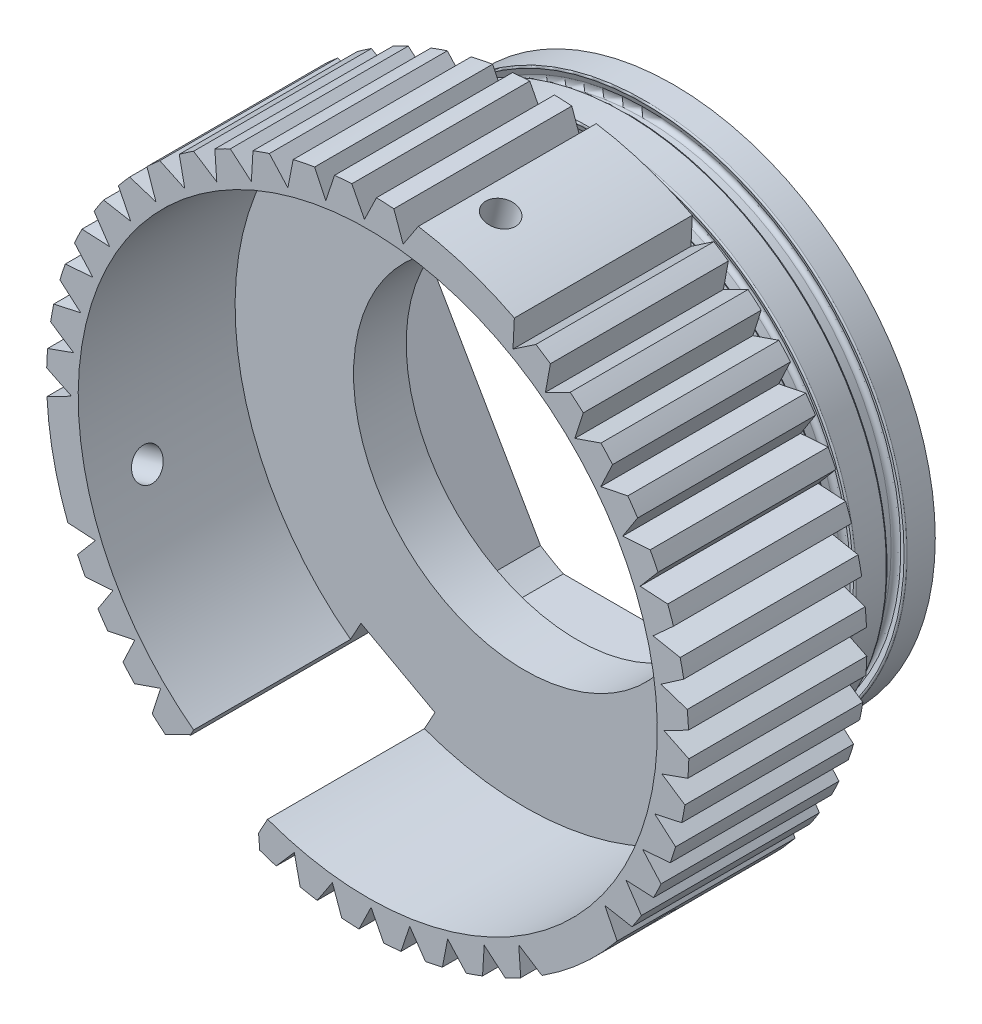
SolidWorks part; units mm, degrees
material "VeroWhite Plus"
ref_plane "Front Plane" through (0, 0, 0) normal (0, 0, 1) x (1, 0, 0)
ref_plane "Top Plane" through (0, 0, 0) normal (0, 1, 0) x (1, 0, 0)
ref_plane "Right Plane" through (0, 0, 0) normal (1, 0, 0) x (0, 0, -1)
sketch "Sketch1" plane through (0, 0, 0) normal (0, 0, 1) x (1, 0, 0)
  circle A0 centre (0, 0) radius 24.875
  dimension "D1" = 49.75
extrude "Boss-Extrude1" add sketch "Sketch1" along normal blind 12.12
sketch "Sketch2" plane through (0, 0, 0) normal (0, 1, 0) x (1, 0, 0)
  line L0 (24.875, -12.12) -> (24.875, 0) construction
  line L1 (24.875, -12.12) -> (24.875, -4.6413) construction
  line L2 (24.6963, -4.5253) -> (24.1354, -4.7751)
  line L3 (23.5771, -4.4125) -> (23.5771, -2.8969)
  line L4 (16.2677, -3.6547) -> (30.8864, -3.6547) construction
  line L5 (24.6963, -2.7841) -> (24.1354, -2.5343)
  line L6 (24.875, -4.6413) -> (24.875, -2.6681)
  line L7 (0, 0) -> (0, -23.2204) construction
  line L8 (23.9739, -2.5) -> (24.1021, -2.5) construction
  line L9 (24.875, 0) -> (-24.875, 0) construction
  line L10 (23.5771, -4.4125) -> (23.5771, -5.8363) construction
  line L11 (23.9739, -4.8094) -> (23.5771, -4.8094) construction
  line L12 (23.5771, -6.0594) -> (25.7057, -6.0594) construction
  line L13 (24.6963, -9.3346) -> (24.1354, -9.5844)
  line L14 (23.5771, -7.7062) -> (23.5771, -9.2218)
  line L15 (24.6963, -7.5934) -> (24.1354, -7.3437)
  line L16 (24.875, -7.4774) -> (24.875, -9.4507)
  line L17 (23.9739, -9.6187) -> (22.6786, -9.6187) construction
  arc A0 (24.1354, -4.7751) -> (23.5771, -4.4125) centre (23.9739, -4.4125) cw
  arc A1 (24.6963, -4.5253) -> (24.875, -4.6413) centre (24.748, -4.6413) cw
  circle A2 centre (24.4661, -3.6547) radius 0.889 construction
  arc A3 (24.1354, -2.5343) -> (23.5771, -2.8969) centre (23.9739, -2.8969) ccw
  arc A4 (24.6963, -2.7841) -> (24.875, -2.6681) centre (24.748, -2.6681) ccw
  arc A5 (24.6963, -9.3346) -> (24.875, -9.4507) centre (24.748, -9.4507) cw
  arc A6 (24.1354, -9.5844) -> (23.5771, -9.2218) centre (23.9739, -9.2218) cw
  arc A7 (24.1354, -7.3437) -> (23.5771, -7.7062) centre (23.9739, -7.7062) ccw
  arc A8 (24.6963, -7.5934) -> (24.875, -7.4774) centre (24.748, -7.4774) ccw
  point P8 (23.5771, -3.6547)
  point P15 (23.5771, -3.6547)
  point P46 (25.3551, -3.6547)
  dimension "D3" = 0.3969
  dimension "D4" = 0.127
  dimension "D5" = 1.778
  dimension "D1" = 1.2979
  dimension "D2" = 66
  dimension "D6" = 2.5
  dimension "D7" = 1.25
revolve "Cut-Revolve1" cut sketch "Sketch2" angle 360 about L7
sketch "Sketch6" plane through (0, 0, 12.12) normal (0, 0, 1) x (1, 0, 0)
  circle A0 centre (0, 0) radius 30.5
  dimension "D1" = 61
extrude "Boss-Extrude2" add sketch "Sketch6" along normal blind 2
sketch "Sketch4" plane through (0, 0, 0) normal (0, 0, 1) x (1, 0, 0)
  circle A0 centre (0, 0) radius 16.25
  dimension "D1" = 32.5
extrude "Cut-Extrude1" cut sketch "Sketch4" along normal through all contours A0
sketch "Sketch5" plane through (0, 0, 0) normal (0, 0, -1) x (-1, 0, 0)
  line L0 (17.7535, 10.25) -> (12.5394, 19.2812) construction
  line L7 (10.4283, 20.5) -> (0, 20.5) construction
  line L8 (22.9677, 1.2188) -> (17.7535, 10.25) construction
  line L9 (17.7535, -10.25) -> (22.9677, -1.2188) construction
  line L10 (12.5394, -19.2812) -> (17.7535, -10.25) construction
  line L11 (0, -20.5) -> (10.4283, -20.5) construction
  line L12 (-10.4283, -20.5) -> (0, -20.5) construction
  line L13 (-17.7535, -10.25) -> (-12.5394, -19.2812) construction
  line L14 (-17.7535, 10.25) -> (-22.9677, 1.2188) construction
  line L15 (-22.9677, -1.2188) -> (-17.7535, -10.25) construction
  line L16 (0, 20.5) -> (-10.4283, 20.5) construction
  line L17 (-12.5394, 19.2812) -> (-17.7535, 10.25) construction
  line L18 (17.8401, 10.3) -> (12.614, 19.3519)
  line L19 (10.4523, 20.6) -> (0, 20.6)
  line L20 (0, 20.6) -> (-10.4523, 20.6)
  line L21 (-12.614, 19.3519) -> (-17.8401, 10.3)
  line L22 (-17.8401, 10.3) -> (-23.0663, 1.2481)
  line L23 (-23.0663, -1.2481) -> (-17.8401, -10.3)
  line L24 (-17.8401, -10.3) -> (-12.614, -19.3519)
  line L25 (-10.4523, -20.6) -> (0, -20.6)
  line L26 (0, -20.6) -> (10.4523, -20.6)
  line L27 (12.614, -19.3519) -> (17.8401, -10.3)
  line L28 (17.8401, -10.3) -> (23.0663, -1.2481)
  line L29 (23.0663, 1.2481) -> (17.8401, 10.3)
  arc A1 (12.5394, 19.2812) -> (10.4283, 20.5) centre (0, 0) ccw construction
  arc A2 (17.7535, 10.25) -> (0, 20.5) centre (0, 0) ccw construction
  arc A3 (22.9677, -1.2188) -> (22.9677, 1.2188) centre (0, 0) ccw construction
  arc A4 (17.7535, -10.25) -> (17.7535, 10.25) centre (0, 0) ccw construction
  arc A5 (0, -20.5) -> (17.7535, -10.25) centre (0, 0) ccw construction
  arc A6 (10.4283, -20.5) -> (12.5394, -19.2812) centre (0, 0) ccw construction
  arc A7 (-17.7535, -10.25) -> (0, -20.5) centre (0, 0) ccw construction
  arc A8 (-12.5394, -19.2812) -> (-10.4283, -20.5) centre (0, 0) ccw construction
  arc A9 (-22.9677, 1.2188) -> (-22.9677, -1.2188) centre (0, 0) ccw construction
  arc A10 (-17.7535, 10.25) -> (-17.7535, -10.25) centre (0, 0) ccw construction
  arc A11 (-10.4283, 20.5) -> (-12.5394, 19.2812) centre (0, 0) ccw construction
  arc A12 (0, 20.5) -> (-17.7535, 10.25) centre (0, 0) ccw construction
  arc A13 (12.614, 19.3519) -> (10.4523, 20.6) centre (0, 0) ccw
  arc A14 (-10.4523, 20.6) -> (-12.614, 19.3519) centre (0, 0) ccw
  arc A15 (-23.0663, 1.2481) -> (-23.0663, -1.2481) centre (0, 0) ccw
  arc A16 (-12.614, -19.3519) -> (-10.4523, -20.6) centre (0, 0) ccw
  arc A17 (10.4523, -20.6) -> (12.614, -19.3519) centre (0, 0) ccw
  arc A18 (23.0663, -1.2481) -> (23.0663, 1.2481) centre (0, 0) ccw
  circle M1 centre (0, 0) radius 16.25
  dimension "D1" = 0.1
extrude "Cut-Extrude2" cut sketch "Sketch5" against normal offset from surface (9.12 mm away) 5 contours L28 A18 L29 L18 A13 L19 L20 A14 L21 L22 A15 L23 L24 A16 L25 L26 A17 L27 M1
sketch "Sketch11" plane through (0, 0, 14.12) normal (0, 0, 1) x (1, 0, 0)
  circle A0 centre (0, 0) radius 27.5
  circle A1 centre (0, 0) radius 30.5
  circle A2 centre (0, 0) radius 30.5
  dimension "D1" = 0
  dimension "D2" = 3
extrude "Boss-Extrude5" add sketch "Sketch11" along normal blind 70
ref_plane "Plane2" through (30.5, 0, 0) normal (1, 0, 0) x (0, 0, -1)
sketch "Sketch14" plane through (0, 0, 84.12) normal (0, 0, 1) x (1, 0, 0)
  line L0 (9.9131, 31.394) -> (7.112, 32.1446) construction
  line L1 (11.113, 31.0725) -> (5.9121, 32.4661) construction
  line L2 (8.5126, 31.7693) -> (0, 0) construction
  line L3 (0, 0) -> (-6.2397, 29.8549) construction
  line L4 (0, 0) -> (-5.194, 30.0545) construction
  line L5 (0, 0) -> (-4.3196, 30.1926) construction
  line L6 (-10.1149, 29.8793) -> (-7.5851, 27.0901) construction
  line L8 (-4.9343, 30.0982) -> (-4.1426, 28.9552) construction
  line L9 (-4.1426, 28.9552) -> (-3.7032, 30.2744) construction
  line L10 (5.9121, 32.4661) -> (4.002, 25.3375) construction
  line L11 (11.113, 31.0725) -> (9.4356, 24.8123) construction
  line L12 (-32.4661, -5.9121) -> (-31.0725, -11.113) construction
  line L13 (-32.1446, -7.112) -> (-31.394, -9.9132) construction
  line L14 (22.2314, -24.282) -> (24.282, -22.2314) construction
  line L15 (-31.7693, -8.5126) -> (0, 0) construction
  line L16 (0, 0) -> (23.2567, -23.2567) construction
  line L17 (25.1604, -21.3531) -> (18.9649, -15.1575) construction
  line L18 (21.3531, -25.1604) -> (14.6891, -18.4965) construction
  line L19 (-32.4661, -5.9121) -> (-24.142, -3.6817) construction
  line L20 (-31.0725, -11.113) -> (-21.737, -8.6116) construction
  line L22 (-0.9635, 30.4848) -> (-0.3278, 29.2482) construction
  line L23 (-0.3278, 29.2482) -> (0.2801, 30.4987) construction
  line L25 (3.0238, 30.3497) -> (3.4927, 29.0407) construction
  line L26 (3.4927, 29.0407) -> (4.2586, 30.2012) construction
  line L28 (14.408, 26.8823) -> (14.3402, 25.4935) construction
  line L29 (14.3402, 25.4935) -> (15.4919, 26.2726) construction
  line L31 (17.7936, 24.7717) -> (17.5451, 23.4037) construction
  line L32 (17.5451, 23.4037) -> (18.7887, 24.0257) construction
  line L34 (20.8747, 22.2373) -> (20.4498, 20.9133) construction
  line L35 (20.4498, 20.9133) -> (21.7639, 21.3678) construction
  line L37 (23.5987, 19.3223) -> (23.0046, 18.0652) construction
  line L38 (23.0046, 18.0652) -> (24.3668, 18.3442) construction
  line L40 (25.9188, 16.0768) -> (25.1658, 14.9079) construction
  line L41 (25.1658, 14.9079) -> (26.5527, 15.0068) construction
  line L43 (27.7956, 12.5562) -> (26.8963, 11.4956) construction
  line L44 (26.8963, 11.4956) -> (28.2843, 11.4126) construction
  line L46 (29.1967, 8.8207) -> (28.1667, 7.8866) construction
  line L47 (28.1667, 7.8866) -> (29.532, 7.6231) construction
  line L49 (30.0982, 4.9343) -> (28.9552, 4.1426) construction
  line L50 (28.9552, 4.1426) -> (30.2744, 3.7032) construction
  line L52 (30.4848, 0.9635) -> (29.2482, 0.3278) construction
  line L53 (29.2482, 0.3278) -> (30.4987, -0.2801) construction
  line L55 (30.3497, -3.0238) -> (29.0407, -3.4927) construction
  line L56 (29.0407, -3.4927) -> (30.2012, -4.2586) construction
  line L58 (29.6954, -6.9594) -> (28.3364, -7.2534) construction
  line L59 (28.3364, -7.2534) -> (29.387, -8.1642) construction
  line L61 (28.533, -10.7759) -> (27.1472, -10.89) construction
  line L62 (27.1472, -10.89) -> (28.0699, -11.9301) construction
  line L64 (26.8823, -14.408) -> (25.4935, -14.3402) construction
  line L65 (25.4935, -14.3402) -> (26.2726, -15.4919) construction
  line L67 (24.7717, -17.7936) -> (23.4037, -17.5451) construction
  line L68 (23.4037, -17.5451) -> (24.0257, -18.7887) construction
  line L70 (16.0768, -25.9189) -> (14.9079, -25.1658) construction
  line L71 (14.9079, -25.1658) -> (15.0068, -26.5527) construction
  line L73 (12.5562, -27.7956) -> (11.4956, -26.8964) construction
  line L74 (11.4956, -26.8964) -> (11.4126, -28.2843) construction
  line L76 (8.8207, -29.1967) -> (7.8866, -28.1667) construction
  line L77 (7.8866, -28.1667) -> (7.6231, -29.532) construction
  line L79 (4.9343, -30.0982) -> (4.1426, -28.9552) construction
  line L80 (4.1426, -28.9552) -> (3.7032, -30.2744) construction
  line L82 (0.9635, -30.4848) -> (0.3278, -29.2482) construction
  line L83 (0.3278, -29.2482) -> (-0.2801, -30.4987) construction
  line L85 (-3.0238, -30.3497) -> (-3.4927, -29.0407) construction
  line L86 (-3.4927, -29.0407) -> (-4.2586, -30.2012) construction
  line L88 (-6.9594, -29.6954) -> (-7.2534, -28.3364) construction
  line L89 (-7.2534, -28.3364) -> (-8.1642, -29.387) construction
  line L91 (-10.7759, -28.533) -> (-10.89, -27.1472) construction
  line L92 (-10.89, -27.1472) -> (-11.9301, -28.0699) construction
  line L94 (-14.408, -26.8823) -> (-14.3402, -25.4935) construction
  line L95 (-14.3402, -25.4935) -> (-15.4919, -26.2726) construction
  line L97 (-17.7936, -24.7717) -> (-17.5451, -23.4037) construction
  line L98 (-17.5451, -23.4037) -> (-18.7887, -24.0257) construction
  line L100 (-20.8747, -22.2373) -> (-20.4498, -20.9133) construction
  line L101 (-20.4498, -20.9133) -> (-21.7639, -21.3678) construction
  line L103 (-23.5987, -19.3223) -> (-23.0046, -18.0652) construction
  line L104 (-23.0046, -18.0652) -> (-24.3668, -18.3442) construction
  line L106 (-25.9188, -16.0768) -> (-25.1658, -14.9079) construction
  line L107 (-25.1658, -14.9079) -> (-26.5527, -15.0068) construction
  line L109 (-27.7956, -12.5562) -> (-26.8964, -11.4956) construction
  line L110 (-26.8964, -11.4956) -> (-28.2843, -11.4126) construction
  line L112 (-30.4848, -0.9635) -> (-29.2482, -0.3278) construction
  line L113 (-29.2482, -0.3278) -> (-30.4987, 0.2801) construction
  line L115 (-30.3497, 3.0238) -> (-29.0407, 3.4927) construction
  line L116 (-29.0407, 3.4927) -> (-30.2012, 4.2586) construction
  line L118 (-29.6954, 6.9594) -> (-28.3364, 7.2534) construction
  line L119 (-28.3364, 7.2534) -> (-29.387, 8.1642) construction
  line L121 (-28.533, 10.7759) -> (-27.1472, 10.89) construction
  line L122 (-27.1472, 10.89) -> (-28.07, 11.9301) construction
  line L124 (-26.8823, 14.408) -> (-25.4935, 14.3402) construction
  line L125 (-25.4935, 14.3402) -> (-26.2726, 15.4919) construction
  line L127 (-24.7717, 17.7936) -> (-23.4037, 17.5451) construction
  line L128 (-23.4037, 17.5451) -> (-24.0257, 18.7887) construction
  line L130 (-22.2373, 20.8747) -> (-20.9133, 20.4498) construction
  line L131 (-20.9133, 20.4498) -> (-21.3678, 21.7639) construction
  line L133 (-19.3223, 23.5987) -> (-18.0652, 23.0046) construction
  line L134 (-18.0652, 23.0046) -> (-18.3442, 24.3668) construction
  line L136 (-16.0768, 25.9188) -> (-14.9079, 25.1658) construction
  line L137 (-14.9079, 25.1658) -> (-15.0068, 26.5527) construction
  line L139 (-12.5562, 27.7955) -> (-11.4956, 26.8963) construction
  line L140 (-11.4956, 26.8963) -> (-11.4126, 28.2843) construction
  line L142 (-8.8207, 29.1967) -> (-7.8866, 28.1667) construction
  line L143 (-7.8866, 28.1667) -> (-7.6231, 29.532) construction
  line L146 (-3.9843, 27.8484) -> (-3.1555, 30.3363)
  line L148 (-1.5142, 30.4624) -> (-0.3152, 28.1302)
  line L149 (-0.3152, 28.1302) -> (0.8311, 30.4887)
  line L151 (2.4749, 30.3994) -> (3.3592, 27.9307)
  line L152 (3.3592, 27.9307) -> (4.8036, 30.1194)
  line L154 (13.9199, 27.1383) -> (13.7921, 24.5191)
  line L155 (13.7921, 24.5191) -> (15.9641, 25.9884)
  line L157 (17.343, 25.0892) -> (16.8745, 22.5091)
  line L158 (16.8745, 22.5091) -> (19.2197, 23.6823)
  line L160 (20.4695, 22.6109) -> (19.6681, 20.114)
  line L161 (19.6681, 20.114) -> (22.1465, 20.971)
  line L163 (23.2457, 19.7456) -> (22.1253, 17.3747)
  line L164 (22.1253, 17.3747) -> (24.6943, 17.9009)
  line L166 (25.6241, 16.5425) -> (24.2038, 14.3381)
  line L167 (24.2038, 14.3381) -> (26.8195, 14.5245)
  line L169 (27.5641, 13.0564) -> (25.8683, 11.0562)
  line L170 (25.8683, 11.0562) -> (28.4859, 10.8996)
  line L172 (29.0325, 9.3468) -> (27.0901, 7.5851)
  line L173 (27.0901, 7.5851) -> (29.6649, 7.0882)
  line L175 (30.0041, 5.4774) -> (27.8484, 3.9843)
  line L176 (27.8484, 3.9843) -> (30.3363, 3.1555)
  line L178 (30.4624, 1.5142) -> (28.1302, 0.3152)
  line L179 (28.1302, 0.3152) -> (30.4887, -0.8312)
  line L181 (30.3994, -2.4749) -> (27.9307, -3.3592)
  line L182 (27.9307, -3.3592) -> (30.1194, -4.8036)
  line L184 (29.8163, -6.4217) -> (27.2533, -6.9761)
  line L185 (27.2533, -6.9761) -> (29.2347, -8.6939)
  line L187 (28.723, -10.2585) -> (26.1095, -10.4737)
  line L188 (26.1095, -10.4737) -> (27.8498, -12.4354)
  line L190 (27.1383, -13.9199) -> (24.5191, -13.7921)
  line L191 (24.5191, -13.7921) -> (25.9884, -15.9641)
  line L193 (25.0892, -17.3431) -> (22.5091, -16.8745)
  line L194 (22.5091, -16.8745) -> (23.6823, -19.2197)
  line L196 (16.5425, -25.6241) -> (14.3381, -24.2039)
  line L197 (14.3381, -24.2039) -> (14.5245, -26.8195)
  line L199 (13.0564, -27.5641) -> (11.0562, -25.8683)
  line L200 (11.0562, -25.8683) -> (10.8996, -28.4859)
  line L202 (9.3468, -29.0325) -> (7.5851, -27.0901)
  line L203 (7.5851, -27.0901) -> (7.0882, -29.6649)
  line L205 (5.4774, -30.0041) -> (3.9843, -27.8484)
  line L206 (3.9843, -27.8484) -> (3.1555, -30.3363)
  line L208 (1.5142, -30.4624) -> (0.3152, -28.1302)
  line L209 (0.3152, -28.1302) -> (-0.8312, -30.4887)
  line L211 (-2.4749, -30.3994) -> (-3.3592, -27.9307)
  line L212 (-3.3592, -27.9307) -> (-4.8036, -30.1194)
  line L214 (-6.4217, -29.8163) -> (-6.9761, -27.2533)
  line L215 (-6.9761, -27.2533) -> (-8.6939, -29.2347)
  line L217 (-10.2585, -28.723) -> (-10.4737, -26.1096)
  line L218 (-10.4737, -26.1096) -> (-12.4354, -27.8498)
  line L220 (-13.9199, -27.1383) -> (-13.7921, -24.5191)
  line L221 (-13.7921, -24.5191) -> (-15.9641, -25.9884)
  line L223 (-17.3431, -25.0892) -> (-16.8745, -22.5091)
  line L224 (-16.8745, -22.5091) -> (-19.2197, -23.6823)
  line L226 (-20.4695, -22.6108) -> (-19.6682, -20.114)
  line L227 (-19.6682, -20.114) -> (-22.1465, -20.971)
  line L229 (-23.2457, -19.7456) -> (-22.1253, -17.3747)
  line L230 (-22.1253, -17.3747) -> (-24.6943, -17.9009)
  line L232 (-25.6241, -16.5425) -> (-24.2039, -14.3381)
  line L233 (-24.2039, -14.3381) -> (-26.8195, -14.5245)
  line L235 (-27.5641, -13.0564) -> (-25.8683, -11.0562)
  line L236 (-25.8683, -11.0562) -> (-28.4859, -10.8996)
  line L238 (-30.4624, -1.5142) -> (-28.1302, -0.3152)
  line L239 (-28.1302, -0.3152) -> (-30.4887, 0.8311)
  line L241 (-30.3994, 2.4749) -> (-27.9307, 3.3592)
  line L242 (-27.9307, 3.3592) -> (-30.1194, 4.8036)
  line L244 (-29.8163, 6.4217) -> (-27.2533, 6.9761)
  line L245 (-27.2533, 6.9761) -> (-29.2347, 8.6939)
  line L247 (-28.723, 10.2585) -> (-26.1096, 10.4737)
  line L248 (-26.1096, 10.4737) -> (-27.8498, 12.4354)
  line L250 (-27.1383, 13.9199) -> (-24.5191, 13.7921)
  line L251 (-24.5191, 13.7921) -> (-25.9884, 15.9641)
  line L253 (-25.0892, 17.343) -> (-22.5091, 16.8745)
  line L254 (-22.5091, 16.8745) -> (-23.6823, 19.2197)
  line L256 (-22.6109, 20.4695) -> (-20.114, 19.6682)
  line L257 (-20.114, 19.6682) -> (-20.971, 22.1465)
  line L259 (-19.7456, 23.2457) -> (-17.3747, 22.1253)
  line L260 (-17.3747, 22.1253) -> (-17.9009, 24.6943)
  line L262 (-16.5425, 25.6241) -> (-14.3381, 24.2038)
  line L263 (-14.3381, 24.2038) -> (-14.5245, 26.8195)
  line L265 (-13.0564, 27.5641) -> (-11.0562, 25.8683)
  line L266 (-11.0562, 25.8683) -> (-10.8996, 28.4859)
  line L268 (-9.3468, 29.0325) -> (-7.5851, 27.0901)
  line L269 (-7.5851, 27.0901) -> (-7.0882, 29.6649)
  line L270 (-25.8683, -11.0562) -> (-29.6271, -10.8314) construction
  line L271 (-26.8964, -11.4956) -> (-28.8494, -11.3788) construction
  line L272 (-28.3035, -13.9284) -> (-25.8683, -11.0562) construction
  line L273 (-28.1617, -12.988) -> (-26.8964, -11.4956) construction
  line L274 (-24.2039, -14.3381) -> (-27.9599, -14.6058) construction
  line L275 (-25.1658, -14.9079) -> (-27.1174, -15.047) construction
  line L276 (-26.2433, -17.5036) -> (-24.2039, -14.3381) construction
  line L277 (-26.2255, -16.5527) -> (-25.1658, -14.9079) construction
  line L278 (-3.5243, 30.8114) -> (-5.2566, 30.5636) construction
  line L279 (-22.1253, -17.3747) -> (-25.8143, -18.1304) construction
  line L280 (-23.0046, -18.0652) -> (-24.9214, -18.4578) construction
  line L281 (-23.8405, -19.8342) -> (-23.0046, -18.0652) construction
  line L282 (-23.7341, -20.7793) -> (-22.1253, -17.3747) construction
  line L283 (-19.6682, -20.114) -> (-23.2269, -21.3447) construction
  line L284 (-20.4498, -20.9133) -> (-22.2989, -21.5528) construction
  line L285 (-21.0477, -22.7763) -> (-20.4498, -20.9133) construction
  line L286 (-20.8188, -23.6994) -> (-19.6682, -20.114) construction
  line L287 (-16.8745, -22.5091) -> (-20.2422, -24.1938) construction
  line L288 (-17.5451, -23.4037) -> (-19.2949, -24.279) construction
  line L289 (-17.8947, -25.3287) -> (-17.5451, -23.4037) construction
  line L290 (-17.5473, -26.2141) -> (-16.8745, -22.5091) construction
  line L291 (-13.7921, -24.5191) -> (-16.9111, -26.629) construction
  line L292 (-14.3402, -25.4935) -> (-15.9608, -26.5898) construction
  line L293 (-13.9756, -28.2802) -> (-13.7921, -24.5191) construction
  line L294 (-14.4356, -27.4478) -> (-14.3402, -25.4935) construction
  line L295 (-11.0562, 25.8683) -> (-10.8314, 29.6271) construction
  line L296 (-10.4737, -26.1096) -> (-13.2906, -28.6085) construction
  line L297 (-10.89, -27.1472) -> (-12.3536, -28.4456) construction
  line L298 (-10.7294, -29.0972) -> (-10.89, -27.1472) construction
  line L299 (-10.1647, -29.8624) -> (-10.4737, -26.1096) construction
  line L300 (-6.9761, -27.2533) -> (-9.4428, -30.0985) construction
  line L301 (-7.2534, -28.3364) -> (-8.535, -29.8147) construction
  line L302 (-6.8397, -30.2487) -> (-7.2534, -28.3364) construction
  line L303 (-6.1799, -30.9337) -> (-6.9761, -27.2533) construction
  line L304 (-3.3592, -27.9307) -> (-5.4333, -31.0735) construction
  line L305 (-28.8494, -11.3788) -> (-28.1617, -12.988) construction
  line L306 (-29.6271, -10.8314) -> (-28.3035, -13.9284) construction
  line L307 (-27.1174, -15.047) -> (-26.2255, -16.5527) construction
  line L308 (-27.9599, -14.6058) -> (-26.2433, -17.5036) construction
  line L309 (-23.2269, -21.3447) -> (-20.8188, -23.6994) construction
  line L310 (-22.2989, -21.5528) -> (-21.0477, -22.7763) construction
  line L311 (-25.8143, -18.1304) -> (-23.7341, -20.7793) construction
  line L312 (-24.9214, -18.4578) -> (-23.8405, -19.8342) construction
  line L313 (-19.2949, -24.279) -> (-17.8947, -25.3287) construction
  line L314 (-20.2422, -24.1938) -> (-17.5473, -26.2141) construction
  line L315 (-15.9608, -26.5898) -> (-14.4356, -27.4478) construction
  line L316 (-16.9111, -26.629) -> (-13.9756, -28.2802) construction
  line L317 (-12.3536, -28.4456) -> (-10.7294, -29.0972) construction
  line L318 (-13.2906, -28.6085) -> (-10.1647, -29.8624) construction
  line L319 (-9.4428, -30.0985) -> (-6.1799, -30.9337) construction
  line L320 (-8.535, -29.8147) -> (-6.8397, -30.2487) construction
  line L321 (-3.4927, -29.0407) -> (-4.5704, -30.6737) construction
  line L322 (-2.8329, -30.8827) -> (-3.4927, -29.0407) construction
  line L323 (-2.0894, -31.4757) -> (-3.3592, -27.9307) construction
  line L324 (-4.5704, -30.6737) -> (-2.8329, -30.8827) construction
  line L325 (-5.4333, -31.0735) -> (-2.0894, -31.4757) construction
  line L326 (0.3152, -28.1302) -> (-1.3309, -31.5169) construction
  line L327 (0.3278, -29.2482) -> (-0.5276, -31.0079) construction
  line L328 (1.2223, -30.9883) -> (0.3278, -29.2482) construction
  line L329 (2.0369, -31.4792) -> (0.3152, -28.1302) construction
  line L330 (-0.5276, -31.0079) -> (1.2223, -30.9883) construction
  line L331 (-1.3309, -31.5169) -> (2.0369, -31.4792) construction
  line L332 (3.9843, -27.8484) -> (2.7942, -31.421) construction
  line L333 (4.1426, -28.9552) -> (3.5243, -30.8114) construction
  line L334 (5.2566, -30.5636) -> (4.1426, -28.9552) construction
  line L335 (6.1283, -30.944) -> (3.9843, -27.8484) construction
  line L336 (3.5243, -30.8114) -> (5.2566, -30.5636) construction
  line L337 (2.7942, -31.421) -> (6.1283, -30.944) construction
  line L338 (7.5851, -27.0901) -> (6.8716, -30.7875) construction
  line L339 (7.8866, -28.1667) -> (7.5158, -30.0878) construction
  line L340 (9.201, -29.616) -> (7.8866, -28.1667) construction
  line L341 (10.1149, -29.8793) -> (7.5851, -27.0901) construction
  line L342 (6.8716, -30.7875) -> (10.1149, -29.8793) construction
  line L343 (7.5158, -30.0878) -> (9.201, -29.616) construction
  line L344 (11.0562, -25.8683) -> (10.8314, -29.6271) construction
  line L345 (11.4956, -26.8964) -> (11.3788, -28.8494) construction
  line L346 (12.988, -28.1617) -> (11.4956, -26.8964) construction
  line L347 (13.9284, -28.3035) -> (11.0562, -25.8683) construction
  line L348 (10.8314, -29.6271) -> (13.9284, -28.3035) construction
  line L349 (11.3788, -28.8494) -> (12.988, -28.1617) construction
  line L350 (14.3381, -24.2039) -> (14.6058, -27.9599) construction
  line L351 (14.9079, -25.1658) -> (15.047, -27.1174) construction
  line L352 (16.5527, -26.2255) -> (14.9079, -25.1658) construction
  line L353 (17.5036, -26.2433) -> (14.3381, -24.2039) construction
  line L354 (15.047, -27.1174) -> (16.5527, -26.2255) construction
  line L355 (14.6058, -27.9599) -> (17.5036, -26.2433) construction
  line L356 (22.5091, -16.8745) -> (24.1938, -20.2422) construction
  line L357 (23.4037, -17.5451) -> (24.279, -19.2949) construction
  line L358 (25.3287, -17.8947) -> (23.4037, -17.5451) construction
  line L359 (26.2141, -17.5473) -> (22.5091, -16.8745) construction
  line L360 (24.5191, -13.7921) -> (26.629, -16.9111) construction
  line L361 (25.4935, -14.3402) -> (26.5898, -15.9608) construction
  line L362 (27.4478, -14.4356) -> (25.4935, -14.3402) construction
  line L363 (28.2802, -13.9756) -> (24.5191, -13.7921) construction
  line L364 (26.5898, -15.9608) -> (27.4478, -14.4356) construction
  line L365 (26.629, -16.9111) -> (28.2802, -13.9756) construction
  line L366 (24.279, -19.2949) -> (25.3287, -17.8947) construction
  line L367 (24.1938, -20.2422) -> (26.2141, -17.5473) construction
  line L368 (26.1095, -10.4737) -> (28.6085, -13.2906) construction
  line L369 (27.1472, -10.89) -> (28.4456, -12.3536) construction
  line L370 (28.4456, -12.3536) -> (29.0972, -10.7294) construction
  line L371 (29.0972, -10.7294) -> (27.1472, -10.89) construction
  line L372 (29.8624, -10.1647) -> (26.1095, -10.4737) construction
  line L373 (28.6085, -13.2906) -> (29.8624, -10.1647) construction
  line L374 (27.2533, -6.9761) -> (30.0985, -9.4428) construction
  line L375 (28.3364, -7.2534) -> (29.8147, -8.535) construction
  line L376 (30.2487, -6.8397) -> (28.3364, -7.2534) construction
  line L377 (30.9337, -6.1799) -> (27.2533, -6.9761) construction
  line L378 (29.8147, -8.535) -> (30.2487, -6.8397) construction
  line L379 (30.0985, -9.4428) -> (30.9337, -6.1799) construction
  line L380 (27.9307, -3.3592) -> (31.0735, -5.4333) construction
  line L381 (29.0407, -3.4927) -> (30.6737, -4.5704) construction
  line L382 (30.6737, -4.5704) -> (30.8827, -2.8329) construction
  line L383 (31.0735, -5.4333) -> (31.4757, -2.0894) construction
  line L384 (30.8827, -2.8329) -> (29.0407, -3.4927) construction
  line L385 (31.4757, -2.0894) -> (27.9307, -3.3592) construction
  line L386 (28.1302, 0.3152) -> (31.5169, -1.3309) construction
  line L387 (29.2482, 0.3278) -> (31.0079, -0.5276) construction
  line L388 (30.9882, 1.2223) -> (29.2482, 0.3278) construction
  line L389 (31.4791, 2.0369) -> (28.1302, 0.3152) construction
  line L390 (27.8484, 3.9843) -> (31.421, 2.7942) construction
  line L391 (28.9552, 4.1426) -> (30.8114, 3.5243) construction
  line L392 (30.5636, 5.2566) -> (28.9552, 4.1426) construction
  line L393 (30.944, 6.1283) -> (27.8484, 3.9843) construction
  line L394 (27.0901, 7.5851) -> (30.7874, 6.8716) construction
  line L395 (28.1667, 7.8866) -> (30.0878, 7.5158) construction
  line L396 (30.0878, 7.5158) -> (29.616, 9.201) construction
  line L397 (30.7874, 6.8716) -> (29.8793, 10.1149) construction
  line L398 (31.421, 2.7942) -> (30.944, 6.1283) construction
  line L399 (30.8114, 3.5243) -> (30.5636, 5.2566) construction
  line L400 (31.0079, -0.5276) -> (30.9882, 1.2223) construction
  line L401 (31.5169, -1.3309) -> (31.4791, 2.0369) construction
  line L402 (29.8793, 10.1149) -> (27.0901, 7.5851) construction
  line L403 (29.616, 9.201) -> (28.1667, 7.8866) construction
  line L404 (25.8683, 11.0562) -> (29.6271, 10.8314) construction
  line L405 (26.8963, 11.4956) -> (28.8494, 11.3788) construction
  line L406 (28.1616, 12.988) -> (26.8963, 11.4956) construction
  line L407 (28.3035, 13.9284) -> (25.8683, 11.0562) construction
  line L408 (24.2038, 14.3381) -> (27.9599, 14.6058) construction
  line L409 (25.1658, 14.9079) -> (27.1174, 15.047) construction
  line L410 (27.1174, 15.047) -> (26.2254, 16.5527) construction
  line L411 (26.2254, 16.5527) -> (25.1658, 14.9079) construction
  line L412 (26.2433, 17.5036) -> (24.2038, 14.3381) construction
  line L413 (27.9599, 14.6058) -> (26.2433, 17.5036) construction
  line L414 (28.8494, 11.3788) -> (28.1616, 12.988) construction
  line L415 (29.6271, 10.8314) -> (28.3035, 13.9284) construction
  line L416 (20.8188, 23.6994) -> (19.6681, 20.114) construction
  line L417 (21.0477, 22.7763) -> (20.4498, 20.9133) construction
  line L418 (20.4498, 20.9133) -> (22.2989, 21.5528) construction
  line L419 (19.6681, 20.114) -> (23.2269, 21.3447) construction
  line L420 (23.7341, 20.7793) -> (22.1253, 17.3747) construction
  line L421 (23.8405, 19.8342) -> (23.0046, 18.0652) construction
  line L422 (23.0046, 18.0652) -> (24.9214, 18.4578) construction
  line L423 (22.1253, 17.3747) -> (25.8143, 18.1304) construction
  line L424 (24.9214, 18.4578) -> (23.8405, 19.8342) construction
  line L425 (25.8143, 18.1304) -> (23.7341, 20.7793) construction
  line L426 (23.2269, 21.3447) -> (20.8188, 23.6994) construction
  line L427 (22.2989, 21.5528) -> (21.0477, 22.7763) construction
  line L428 (13.9756, 28.2802) -> (13.7921, 24.5191) construction
  line L429 (14.4356, 27.4478) -> (14.3402, 25.4935) construction
  line L430 (14.3402, 25.4935) -> (15.9608, 26.5898) construction
  line L431 (13.7921, 24.5191) -> (16.9111, 26.629) construction
  line L432 (17.5473, 26.2141) -> (16.8745, 22.5091) construction
  line L433 (17.8947, 25.3287) -> (17.5451, 23.4037) construction
  line L434 (17.5451, 23.4037) -> (19.2949, 24.279) construction
  line L435 (16.8745, 22.5091) -> (20.2422, 24.1938) construction
  line L436 (20.2422, 24.1938) -> (17.5473, 26.2141) construction
  line L437 (19.2949, 24.279) -> (17.8947, 25.3287) construction
  line L438 (16.9111, 26.629) -> (13.9756, 28.2802) construction
  line L439 (15.9608, 26.5898) -> (14.4356, 27.4478) construction
  line L440 (3.3592, 27.9307) -> (5.4333, 31.0735) construction
  line L441 (3.4927, 29.0407) -> (4.5704, 30.6737) construction
  line L442 (2.8329, 30.8827) -> (3.4927, 29.0407) construction
  line L443 (2.0894, 31.4757) -> (3.3592, 27.9307) construction
  line L444 (-0.3152, 28.1302) -> (1.3309, 31.5169) construction
  line L445 (-0.3278, 29.2482) -> (0.5276, 31.0079) construction
  line L446 (-1.2223, 30.9882) -> (-0.3278, 29.2482) construction
  line L447 (-2.0369, 31.4792) -> (-0.3152, 28.1302) construction
  line L448 (1.3309, 31.5169) -> (-2.0369, 31.4792) construction
  line L449 (0.5276, 31.0079) -> (-1.2223, 30.9882) construction
  line L450 (4.5704, 30.6737) -> (2.8329, 30.8827) construction
  line L451 (5.4333, 31.0735) -> (2.0894, 31.4757) construction
  line L452 (-3.9843, 27.8484) -> (-2.7942, 31.421) construction
  line L453 (-4.1426, 28.9552) -> (-3.5243, 30.8114) construction
  line L454 (-11.4956, 26.8963) -> (-11.3788, 28.8494) construction
  line L455 (-5.2566, 30.5636) -> (-4.1426, 28.9552) construction
  line L456 (-5.0434, 30.0801) -> (-3.9843, 27.8484)
  line L457 (-6.1283, 30.944) -> (-3.9843, 27.8484) construction
  line L458 (-12.988, 28.1616) -> (-11.4956, 26.8963) construction
  line L459 (-7.5851, 27.0901) -> (-6.8716, 30.7875) construction
  line L460 (-7.8866, 28.1667) -> (-7.5158, 30.0878) construction
  line L461 (-7.5158, 30.0878) -> (-9.201, 29.616) construction
  line L462 (-6.8716, 30.7875) -> (-10.1149, 29.8793) construction
  line L463 (-9.201, 29.616) -> (-7.8866, 28.1667) construction
  line L464 (-13.9284, 28.3035) -> (-11.0562, 25.8683) construction
  line L465 (-14.3381, 24.2038) -> (-14.6058, 27.9599) construction
  line L466 (-2.7942, 31.421) -> (-6.1283, 30.944) construction
  line L467 (-14.9079, 25.1658) -> (-15.047, 27.1174) construction
  line L468 (-16.5527, 26.2255) -> (-14.9079, 25.1658) construction
  line L469 (-17.5036, 26.2433) -> (-14.3381, 24.2038) construction
  line L470 (-14.6058, 27.9599) -> (-17.5036, 26.2433) construction
  line L471 (-15.047, 27.1174) -> (-16.5527, 26.2255) construction
  line L472 (-11.3788, 28.8494) -> (-12.988, 28.1616) construction
  line L473 (-10.8314, 29.6271) -> (-13.9284, 28.3035) construction
  line L474 (-17.3747, 22.1253) -> (-18.1304, 25.8143) construction
  line L475 (-18.0652, 23.0046) -> (-18.4578, 24.9214) construction
  line L476 (-19.8342, 23.8405) -> (-18.0652, 23.0046) construction
  line L477 (-20.7793, 23.7341) -> (-17.3747, 22.1253) construction
  line L478 (-18.4578, 24.9214) -> (-19.8342, 23.8405) construction
  line L479 (-18.1304, 25.8143) -> (-20.7793, 23.7341) construction
  line L480 (-21.5528, 22.2989) -> (-22.7763, 21.0477) construction
  line L481 (-21.3447, 23.2269) -> (-23.6994, 20.8188) construction
  line L482 (-20.9133, 20.4498) -> (-21.5528, 22.2989) construction
  line L483 (-22.7763, 21.0477) -> (-20.9133, 20.4498) construction
  line L484 (-20.114, 19.6682) -> (-21.3447, 23.2269) construction
  line L485 (-23.6994, 20.8188) -> (-20.114, 19.6682) construction
  line L486 (-22.5091, 16.8745) -> (-24.1938, 20.2422) construction
  line L487 (-23.4037, 17.5451) -> (-24.279, 19.2949) construction
  line L488 (-25.3287, 17.8947) -> (-23.4037, 17.5451) construction
  line L489 (-26.2141, 17.5473) -> (-22.5091, 16.8745) construction
  line L490 (-24.5191, 13.7921) -> (-26.629, 16.9111) construction
  line L491 (-25.4935, 14.3402) -> (-26.5898, 15.9608) construction
  line L492 (-27.4478, 14.4356) -> (-25.4935, 14.3402) construction
  line L493 (-28.2802, 13.9756) -> (-24.5191, 13.7921) construction
  line L494 (-26.629, 16.9111) -> (-28.2802, 13.9756) construction
  line L495 (-26.5898, 15.9608) -> (-27.4478, 14.4356) construction
  line L496 (-24.1938, 20.2422) -> (-26.2141, 17.5473) construction
  line L497 (-24.279, 19.2949) -> (-25.3287, 17.8947) construction
  line L498 (-26.1096, 10.4737) -> (-28.6085, 13.2906) construction
  line L499 (-27.1472, 10.89) -> (-28.4456, 12.3536) construction
  line L500 (-29.0972, 10.7294) -> (-27.1472, 10.89) construction
  line L501 (-29.8624, 10.1647) -> (-26.1096, 10.4737) construction
  line L502 (-27.2533, 6.9761) -> (-30.0985, 9.4428) construction
  line L503 (-28.3364, 7.2534) -> (-29.8147, 8.535) construction
  line L504 (-30.2487, 6.8397) -> (-28.3364, 7.2534) construction
  line L505 (-30.9337, 6.1799) -> (-27.2533, 6.9761) construction
  line L506 (-30.0985, 9.4428) -> (-30.9337, 6.1799) construction
  line L507 (-29.8147, 8.535) -> (-30.2487, 6.8397) construction
  line L508 (-28.6085, 13.2906) -> (-29.8624, 10.1647) construction
  line L509 (-28.4456, 12.3536) -> (-29.0972, 10.7294) construction
  line L510 (-27.9307, 3.3592) -> (-31.0735, 5.4333) construction
  line L511 (-29.0407, 3.4927) -> (-30.6737, 4.5704) construction
  line L512 (-30.8827, 2.8329) -> (-29.0407, 3.4927) construction
  line L513 (-31.4757, 2.0894) -> (-27.9307, 3.3592) construction
  line L514 (-28.1302, -0.3152) -> (-31.5169, 1.3309) construction
  line L515 (-29.2482, -0.3278) -> (-31.0079, 0.5276) construction
  line L516 (-30.9883, -1.2223) -> (-29.2482, -0.3278) construction
  line L517 (-31.4792, -2.0369) -> (-28.1302, -0.3152) construction
  line L518 (-31.5169, 1.3309) -> (-31.4792, -2.0369) construction
  line L519 (-31.0079, 0.5276) -> (-30.9883, -1.2223) construction
  line L520 (-31.0735, 5.4333) -> (-31.4757, 2.0894) construction
  line L521 (-30.6737, 4.5704) -> (-30.8827, 2.8329) construction
  arc A0 (21.3531, -25.1604) -> (25.1604, -21.3531) centre (0, 0) ccw construction
  arc A1 (-10.2585, -28.723) -> (-8.6939, -29.2347) centre (0, 0) ccw
  circle A2 centre (0, 0) radius 30.5 construction
  arc A3 (-6.4217, -29.8163) -> (-4.8036, -30.1194) centre (0, 0) ccw
  arc A4 (-13.9199, -27.1383) -> (-12.4354, -27.8498) centre (0, 0) ccw
  arc A5 (-17.3431, -25.0892) -> (-15.9641, -25.9884) centre (0, 0) ccw
  arc A6 (-20.4695, -22.6108) -> (-19.2197, -23.6823) centre (0, 0) ccw
  arc A7 (-23.2457, -19.7456) -> (-22.1465, -20.971) centre (0, 0) ccw
  arc A8 (-25.6241, -16.5425) -> (-24.6943, -17.9009) centre (0, 0) ccw
  arc A9 (-27.5641, -13.0564) -> (-26.8195, -14.5245) centre (0, 0) ccw
  arc A10 (-2.4749, -30.3994) -> (-0.8312, -30.4887) centre (0, 0) ccw
  arc A11 (1.5142, -30.4624) -> (3.1555, -30.3363) centre (0, 0) ccw
  arc A12 (5.4774, -30.0041) -> (7.0882, -29.6649) centre (0, 0) ccw
  arc A13 (9.3468, -29.0325) -> (10.8996, -28.4859) centre (0, 0) ccw
  arc A14 (13.0564, -27.5641) -> (14.5245, -26.8195) centre (0, 0) ccw
  arc A15 (16.5425, -25.6241) -> (23.6823, -19.2197) centre (0, 0) ccw
  arc A16 (25.0892, -17.3431) -> (25.9884, -15.9641) centre (0, 0) ccw
  arc A17 (28.723, -10.2585) -> (29.2347, -8.6939) centre (0, 0) ccw
  arc A18 (27.1383, -13.9199) -> (27.8498, -12.4354) centre (0, 0) ccw
  arc A19 (29.8163, -6.4217) -> (30.1194, -4.8036) centre (0, 0) ccw
  arc A20 (30.3994, -2.4749) -> (30.4887, -0.8312) centre (0, 0) ccw
  arc A21 (30.4624, 1.5142) -> (30.3363, 3.1555) centre (0, 0) ccw
  arc A22 (30.0041, 5.4774) -> (29.6649, 7.0882) centre (0, 0) ccw
  arc A23 (29.0325, 9.3468) -> (28.4859, 10.8996) centre (0, 0) ccw
  arc A24 (27.5641, 13.0564) -> (26.8195, 14.5245) centre (0, 0) ccw
  arc A25 (25.6241, 16.5425) -> (24.6943, 17.9009) centre (0, 0) ccw
  arc A26 (23.2457, 19.7456) -> (22.1465, 20.971) centre (0, 0) ccw
  arc A27 (20.4695, 22.6109) -> (19.2197, 23.6823) centre (0, 0) ccw
  arc A28 (13.9199, 27.1383) -> (4.8036, 30.1194) centre (0, 0) ccw
  arc A29 (17.343, 25.0892) -> (15.9641, 25.9884) centre (0, 0) ccw
  arc A30 (2.4749, 30.3994) -> (0.8311, 30.4887) centre (0, 0) ccw
  arc A31 (-1.5142, 30.4624) -> (-3.1555, 30.3363) centre (0, 0) ccw
  arc A32 (-5.0434, 30.0801) -> (-7.0882, 29.6649) centre (0, 0) ccw
  arc A33 (-9.3468, 29.0325) -> (-10.8996, 28.4859) centre (0, 0) ccw
  arc A34 (-13.0564, 27.5641) -> (-14.5245, 26.8195) centre (0, 0) ccw
  arc A35 (-16.5425, 25.6241) -> (-17.9009, 24.6943) centre (0, 0) ccw
  arc A36 (-19.7456, 23.2457) -> (-20.971, 22.1465) centre (0, 0) ccw
  arc A37 (-22.6109, 20.4695) -> (-23.6823, 19.2197) centre (0, 0) ccw
  arc A38 (-25.0892, 17.343) -> (-25.9884, 15.9641) centre (0, 0) ccw
  arc A39 (-27.1383, 13.9199) -> (-27.8498, 12.4354) centre (0, 0) ccw
  arc A40 (-28.723, 10.2585) -> (-29.2347, 8.6939) centre (0, 0) ccw
  arc A41 (-29.8163, 6.4217) -> (-30.1194, 4.8036) centre (0, 0) ccw
  arc A42 (-30.3994, 2.4749) -> (-30.4887, 0.8311) centre (0, 0) ccw
  arc A43 (-30.4624, -1.5142) -> (-28.4859, -10.8996) centre (0, 0) ccw
  circle A44 centre (0, 0) radius 73.8081
  dimension "D1" = 26.805
  dimension "D2" = 2
  dimension "D6" = 0.5
extrude "Cut-Extrude6" cut sketch "Sketch14" against normal up to surface (72 mm away) up to face at (24.875, 0, 12.12)
ref_plane "Plane3" through (-15.25, -26.4138, 0) normal (-0.5, -0.866, 0) x (0, 0, -1)
ref_plane "Plane4" through (0, 0, 0) normal (-0.866, -0.5, 0) x (0, 0, 1)
ref_plane "Plane5" through (15.25, -26.4138, 0) normal (0.5, -0.866, 0) x (-0.866, -0.5, 0)
sketch "Sketch15" plane through (15.25, -26.4138, 0) normal (0.5, -0.866, 0) x (-0.866, -0.5, 0)
  line L1 (-27.5, -84.12) -> (27.5, -84.12) construction
  line L2 (-27.5, -84.12) -> (27.5, -84.12) construction
  line L3 (0, -84.12) -> (-1.2481, 0) construction
  circle A0 centre (-0.3579, -60) radius 3.25
  dimension "D1" = 6.5
  dimension "D2" = 24.12
extrude "Cut-Extrude7" cut sketch "Sketch15" against normal up to next
ref_plane "Plane7" through (13.75, -23.8157, 0) normal (-0.5, 0.866, 0) x (0.866, 0.5, 0)
sketch "Sketch17" plane through (13.75, -23.8157, 0) normal (-0.5, 0.866, 0) x (0.866, 0.5, 0)
  circle A0 centre (0.3579, -60) radius 3.25 construction
  circle A1 centre (0.3579, -60) radius 3.25 construction
  circle A3 centre (0.3579, -60) radius 5
  circle A4 centre (0.3579, -60) radius 6.5
  dimension "D1" = 10
  dimension "D2" = 1.5
extrude "Boss-Extrude6" add sketch "Sketch17" along normal blind 10
sketch "Sketch21" plane through (8.75, -15.1554, 0) normal (-0.5, 0.866, 0) x (0.866, 0.5, 0)
  circle A0 centre (0.3579, -60) radius 5 construction
  circle A1 centre (0.3579, -60) radius 5
sketch "Sketch23" plane through (8.75, -15.1554, 0) normal (-0.5, 0.866, 0) x (0.866, 0.5, 0)
  line L0 (-8.8921, -50.75) -> (-8.8921, -69.25)
  line L1 (-7.3921, -52.25) -> (8.1079, -52.25)
  line L2 (-7.3921, -52.25) -> (-7.3921, -67.75)
  line L3 (-7.3921, -67.75) -> (8.1079, -67.75)
  line L4 (8.1079, -52.25) -> (8.1079, -67.75)
  line L5 (-7.3921, -52.25) -> (8.1079, -67.75) construction
  line L6 (-7.3921, -67.75) -> (8.1079, -52.25) construction
  line L7 (-8.8921, -69.25) -> (9.6079, -69.25)
  line L8 (9.6079, -50.75) -> (9.6079, -69.25)
  line L9 (-8.8921, -50.75) -> (9.6079, -50.75)
  point P0 (0.3579, -60)
  dimension "D1" = 15.5
  dimension "D2" = 15.5
  dimension "D3" = 1.5
extrude "Boss-Extrude7" add sketch "Sketch23" along normal blind 10 separate body
sketch "Sketch24" plane through (8.75, -15.1554, 0) normal (0.5, -0.866, 0) x (0.866, 0.5, 0)
  line L0 (8.1079, 52.25) -> (-7.3921, 52.25) construction
  line L1 (8.1079, 67.75) -> (8.1079, 52.25) construction
  line L2 (-7.3921, 67.75) -> (8.1079, 67.75) construction
  line L3 (-7.3921, 52.25) -> (-7.3921, 67.75) construction
  line L4 (8.1079, 52.25) -> (-7.3921, 52.25)
  line L5 (8.1079, 67.75) -> (8.1079, 52.25)
  line L6 (-7.3921, 67.75) -> (8.1079, 67.75)
  line L7 (-7.3921, 52.25) -> (-7.3921, 67.75)
  circle A0 centre (0.3579, 60) radius 6.5 construction
  circle A1 centre (0.3579, 60) radius 6.5
extrude "Boss-Extrude8" add sketch "Sketch24" along normal blind 1
fillet "Fillet1" radius 2 2 edges at (3.9308, -19.0925, 60) (8.21, -26.2459, 58.71)
fillet "Fillet4" radius 1 4 edges at (-1.4508, -15.2714, 50.75) (14.5707, -6.0214, 50.75) (14.5707, -6.0214, 69.25) (-1.4508, -15.2714, 69.25)
sketch "Sketch25" plane through (0, 0, 84.12) normal (0, 0, 1) x (1, 0, 0)
  circle A0 centre (0, 0) radius 43.5392
extrude "Cut-Extrude9" cut sketch "Sketch25" against normal offset from surface (55.1 mm away) 16.9
ref_plane "Plane8" through (8.2863, -28.7705, -136.0575) normal (0.4788, 0.8779, 0) x (-0.8779, 0.4788, 0)
sketch "Sketch28" plane through (8.2863, -28.7705, -136.0575) normal (0.4788, 0.8779, 0) x (-0.8779, 0.4788, 0)
  line L0 (17.05, 181.33) -> (25.05, 181.33) construction
  line L1 (17.05, 181.33) -> (25.05, 181.33)
sketch "Sketch29" plane through (0, 0, 29.02) normal (0, 0, 1) x (1, 0, 0)
  line L0 (-6.6823, -20.607) -> (-13.7057, -16.7766) construction
  line L1 (-6.6823, -20.607) -> (-13.7057, -16.7766) construction
  line L2 (-15.5437, -20.1467) -> (-16.8957, -22.6258)
  line L4 (-10.2585, -28.723) -> (-10.4737, -26.1096) construction
  line L5 (-10.4737, -26.1096) -> (-12.4354, -27.8498) construction
  line L6 (-13.9199, -27.1383) -> (-13.7921, -24.5191) construction
  line L7 (-13.7921, -24.5191) -> (-15.9641, -25.9884) construction
  line L8 (-17.3431, -25.0892) -> (-16.8745, -22.5091) construction
  line L10 (-10.37, -27.3689) -> (-10.4737, -26.1096)
  line L11 (-10.4737, -26.1096) -> (-12.4354, -27.8498)
  line L12 (-13.9199, -27.1383) -> (-13.7921, -24.5191)
  line L13 (-13.7921, -24.5191) -> (-15.9641, -25.9884)
  line L14 (-17.3431, -25.0892) -> (-16.8957, -22.6258)
  line L15 (-8.5202, -23.9771) -> (-10.37, -27.3689)
  line L16 (-9.9566, -26.6108) -> (-17.6276, -22.4273) construction
  line L17 (-15.5437, -20.1467) -> (-8.5202, -23.9771)
  arc A1 (-13.9199, -27.1383) -> (-12.4354, -27.8498) centre (0, 0) ccw construction
  arc A2 (-17.3431, -25.0892) -> (-15.9641, -25.9884) centre (0, 0) ccw construction
  arc A4 (-13.9199, -27.1383) -> (-12.4354, -27.8498) centre (0, 0) ccw
  arc A5 (-17.3431, -25.0892) -> (-15.9641, -25.9884) centre (0, 0) ccw
  point P15 (-13.7921, -24.5191)
  dimension "D1" = 3
extrude "Cut-Extrude11" cut sketch "Sketch29" against normal through all
ref_plane "Plane9" through (23.8153, -22.6844, 0) normal (-0.7241, 0.6897, 0) x (0, 0, 1)
sketch "Sketch30" plane through (23.8153, -22.6844, 0) normal (-0.7241, 0.6897, 0) x (0, 0, 1)
  circle A1 centre (23.5725, 0) radius 2.7051
  circle A2 centre (23.5725, 0) radius 2.7051 construction
  circle A4 centre (23.5725, 0) radius 1.45
  dimension "D2" = 2.9
  dimension "D1" = 0
extrude "Cut-Extrude12" cut sketch "Sketch30" along normal blind 10
pattern_circular "CirPattern1" count 3 over 360 about axis through (0, 0, 29.02) along (0, 0, 1) of "Cut-Extrude12"
